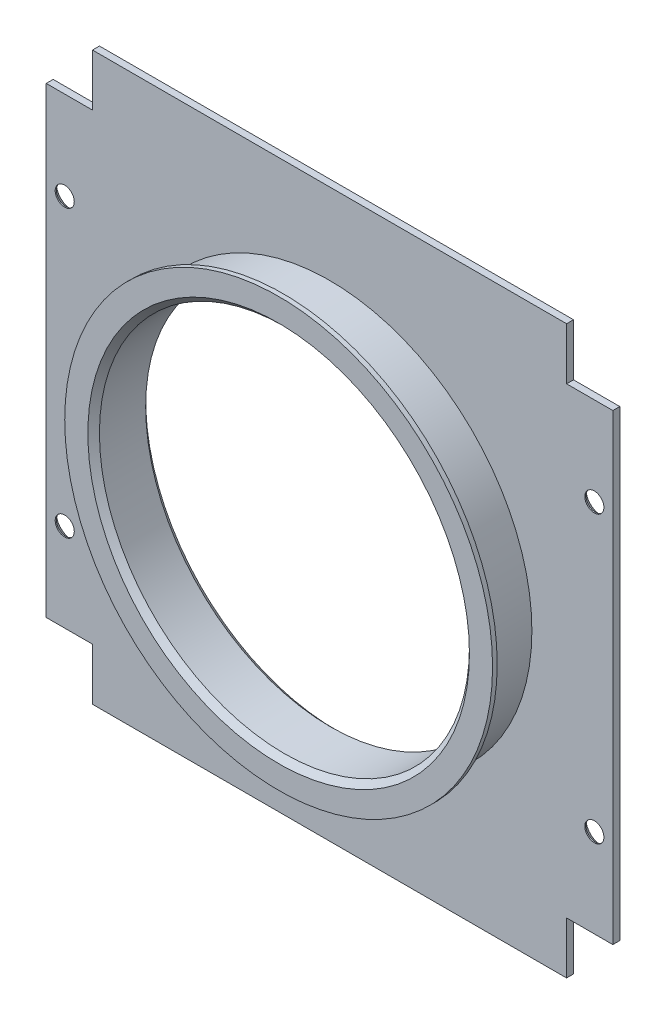
SolidWorks part; units mm, degrees
ref_plane "Front Plane" through (0, 0, 0) normal (1, 0, 0) x (0, 1, 0)
ref_plane "Top Plane" through (0, 0, 0) normal (0, 0, 1) x (0, 1, 0)
ref_plane "Right Plane" through (0, 0, 0) normal (0, 1, 0) x (-1, 0, 0)
sketch "Sketch1" plane through (0, 0, 0) normal (0, 0, 1) x (0, 1, 0)
  line L0 (0, 8) -> (9, 8)
  line L1 (9, 8) -> (9, 0)
  line L2 (9, 0) -> (89, 0)
  line L3 (89, 0) -> (89, 8)
  line L4 (89, 8) -> (98, 8)
  line L5 (98, 8) -> (98, 90)
  line L6 (98, 90) -> (89, 90)
  line L7 (89, 90) -> (89, 98)
  line L8 (89, 98) -> (9, 98)
  line L9 (9, 98) -> (9, 90)
  line L10 (9, 90) -> (0, 90)
  line L11 (0, 90) -> (0, 8)
  dimension "D1" = 98
  dimension "D2" = 8
  dimension "D3" = 90
  dimension "D4" = 9
  dimension "D5" = 89
  dimension "D6" = 98
extrude "Boss-Extrude1" add sketch "Sketch1" along normal blind 1.2 contours L11 L0 L1 L2 L3 L4 L5 L6 L7 L8 L9 L10
sketch "Sketch2" plane through (0, 0, 1.2) normal (0, 0, 1) x (1, 0, 0)
  line L0 (0, 9) -> (0, 89) construction
  line L1 (-94.8, 73.7) -> (-3.2, 73.7) construction
  line L2 (-94.8, 73.7) -> (-94.8, 24.3) construction
  line L3 (-94.8, 24.3) -> (-3.2, 24.3) construction
  line L4 (-3.2, 73.7) -> (-3.2, 24.3) construction
  line L5 (-90, 0) -> (-8, 0) construction
  circle A0 centre (-94.8, 73.7) radius 1.65
  circle A1 centre (-94.8, 24.3) radius 1.65
  circle A2 centre (-3.2, 24.3) radius 1.65
  circle A3 centre (-3.2, 73.7) radius 1.65
  dimension "D5" = 3.3
  dimension "D1" = 3.2
  dimension "D2" = 24.3
  dimension "D3" = 49.4
  dimension "D4" = 91.6
extrude "Cut-Extrude1" cut sketch "Sketch2" against normal blind 1.2
sketch "Sketch3" plane through (0, 0, 1.2) normal (0, 0, 1) x (1, 0, 0)
  line L0 (0, 9) -> (0, 89) construction
  line L1 (-90, 0) -> (-8, 0) construction
  circle A0 centre (-49, 49) radius 35
  dimension "D3" = 70
  dimension "D1" = 49
  dimension "D2" = 49
extrude "Boss-Extrude2" add sketch "Sketch3" along normal blind 8
sketch "Sketch5" plane through (0, 0, 9.2) normal (0, 0, 1) x (1, 0, 0)
  circle A0 centre (-49, 49) radius 37
  circle A1 centre (-49, 49) radius 35 construction
  dimension "D1" = 74
extrude "Boss-Extrude3" add sketch "Sketch5" along normal blind 0.8 contours A0
sketch "Sketch6" plane through (0, 0, 10) normal (0, 0, 1) x (1, 0, 0)
  circle A0 centre (-49, 49) radius 32
  circle A1 centre (-49, 49) radius 37 construction
  dimension "D1" = 64
extrude "Cut-Extrude2" cut sketch "Sketch6" against normal through all
chamfer "Chamfer1" distance 1 angle 45 4 edges at (-1.55, 24.3, 0) (-1.55, 73.7, 0) (-93.15, 73.7, 0) (-93.15, 24.3, 0)
chamfer "Chamfer2" distance 1 angle 45 2 edges at (-17, 49, 10) (-17, 49, 0)
